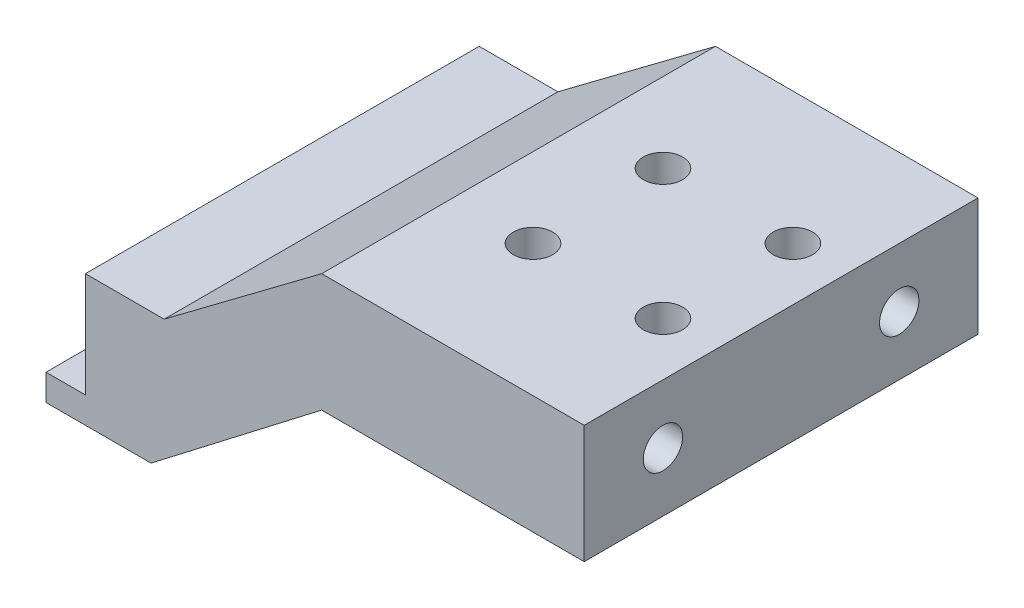
SolidWorks part; units mm, degrees
ref_plane "Спереди" through (0, 0, 0) normal (0, 0, 1) x (1, 0, 0)
ref_plane "Сверху" through (0, 0, 0) normal (0, 1, 0) x (1, 0, 0)
ref_plane "Справа" through (0, 0, 0) normal (1, 0, 0) x (0, 0, -1)
sketch "Эскиз1" plane through (0, 0, 0) normal (0, 1, 0) x (1, 0, 0)
  line L0 (32, 15) -> (25.9896, 21.0104) construction
  line L1 (0, 0) -> (41, 0)
  line L2 (0, 0) -> (0, 30)
  line L3 (0, 30) -> (41, 30)
  line L4 (41, 0) -> (41, 30)
  line L5 (32, 15) -> (32, 25.5625) construction
  line L6 (32, 15) -> (38.0104, 21.0104) construction
  line L7 (32, 15) -> (38.0104, 8.9896) construction
  line L8 (32, 15) -> (25.9896, 8.9896) construction
  circle A0 centre (32, 15) radius 7 construction
  circle A1 centre (32, 15) radius 8.5 construction
  circle A2 centre (36.9497, 19.9497) radius 1.5
  circle A3 centre (27.0503, 19.9497) radius 1.5
  circle A4 centre (36.9497, 10.0503) radius 1.5
  circle A5 centre (27.0503, 10.0503) radius 1.5
  dimension "D3" = 15
  dimension "D5" = 14
  dimension "D6" = 17
  dimension "D1" = 41
  dimension "D2" = 30
  dimension "D4" = 9
  dimension "D7" = 45
extrude "Бобышка-Вытянуть1" add sketch "Эскиз1" along normal blind 10
sketch "Эскиз3" plane through (0, 0, 0) normal (-1, 0, 0) x (0, 0, 1)
  line L0 (-30, 10) -> (0, 10) construction
  line L1 (-30, 10) -> (0, 10)
  line L2 (-30, 10) -> (-30, 2)
  line L3 (-30, 2) -> (0, 2)
  line L4 (0, 10) -> (0, 2)
  line L5 (-30, 0) -> (0, 0) construction
  point P6 (-15, 10)
  point P9 (-15, 0)
  dimension "D1" = 8
  dimension "D2" = 30
extrude "Вырез-Вытянуть2" cut sketch "Эскиз3" against normal blind 3
sketch "Эскиз4" plane through (0, 0, 0) normal (-1, 0, 0) x (0, 0, 1)
  line L0 (-20, 5.4) -> (-9, 5.4) construction
  line L1 (0, 10) -> (-30, 10) construction
  line L2 (-20, 4.4) -> (-10, 4.4) construction
  circle A0 centre (-20, 5.4) radius 1
  circle A1 centre (-10, 5.4) radius 1
  point P5 (-15, 10)
  dimension "D1" = 5
  dimension "D2" = 2
  dimension "D3" = 10
  dimension "D4" = 4.6
extrude "Вырез-Вытянуть3" cut sketch "Эскиз4" against normal blind 7
sketch "Эскиз7" plane through (0, 0, -30) normal (0, 0, -1) x (-1, 0, 0)
  line L0 (-41, 10) -> (-41, 19)
  line L1 (-41, 19) -> (-21, 19)
  line L2 (-21, 19) -> (-9, 10)
  line L3 (-41, 10) -> (-3, 10) construction
  line L4 (-41, 10) -> (-9, 10)
  dimension "D1" = 12
  dimension "D2" = 9
  dimension "D3" = 20
extrude "Бобышка-Вытянуть3" add sketch "Эскиз7" against normal blind 30
sketch "Эскиз6" plane through (0, 0, 0) normal (0, -1, 0) x (1, 0, 0)
  line L0 (0, 0) -> (41, 0) construction
  line L1 (41, -30) -> (21, -30)
  line L2 (41, -30) -> (41, 0)
  line L3 (41, 0) -> (21, 0)
  line L4 (21, -30) -> (21, 0)
  dimension "D1" = 20
extrude "Вырез-Вытянуть5" cut sketch "Эскиз6" against normal blind 10
sketch "Эскиз2" plane through (41, 0, 0) normal (1, 0, 0) x (0, 0, -1)
  line L0 (0, 14.5) -> (30, 14.5) construction
  line L1 (0, 19) -> (0, 10) construction
  line L2 (30, 19) -> (30, 10) construction
  circle A0 centre (6, 14.5) radius 1.5
  circle A1 centre (24, 14.5) radius 1.5
  dimension "D1" = 3
  dimension "D2" = 3
  dimension "D3" = 6
  dimension "D4" = 18
extrude "Вырез-Вытянуть1" cut sketch "Эскиз2" against normal blind 6
sketch "Эскиз8" plane through (0, 19, 0) normal (0, 1, 0) x (1, 0, 0)
  line L0 (32, 15) -> (39.718, 22.718) construction
  line L1 (41, 0) -> (41, 30) construction
  line L2 (21, 0) -> (41, 0) construction
  line L3 (32, 15) -> (43.7004, 15) construction
  circle A0 centre (32, 15) radius 7 construction
  circle A1 centre (32, 15) radius 8.5 construction
  circle A2 centre (36.9497, 19.9497) radius 1.5
  circle A3 centre (36.9497, 10.0503) radius 1.5
  circle A4 centre (27.0503, 10.0503) radius 1.5
  circle A5 centre (27.0503, 19.9497) radius 1.5
  point P20 (32, 15)
  dimension "D1" = 14
  dimension "D2" = 17
  dimension "D6" = 4
  dimension "D3" = 9
  dimension "D4" = 15
  dimension "D5" = 45
extrude "Вырез-Вытянуть6" cut sketch "Эскиз8" against normal through all
sketch "Эскиз9" plane through (0, 0, -30) normal (0, 0, -1) x (-1, 0, 0)
  line L0 (-21, 10) -> (-21, 0)
  line L1 (-21, 10) -> (-21, 0) construction
  line L2 (-21, 0) -> (-8, 0)
  line L3 (-21, 0) -> (0, 0) construction
  line L4 (-8, 0) -> (-21, 10)
  dimension "D1" = 13
extrude "Вырез-Вытянуть7" cut sketch "Эскиз9" against normal through all
